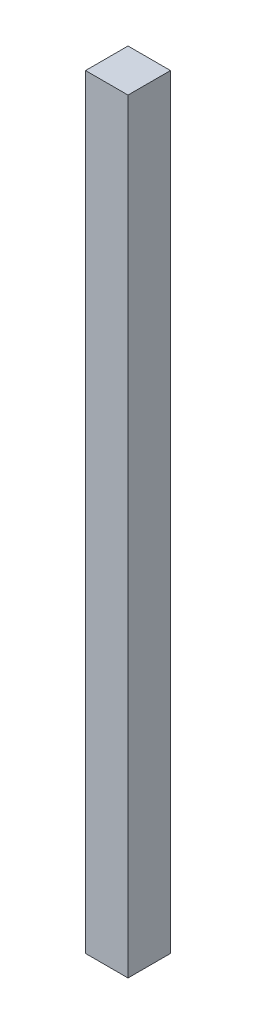
SolidWorks part; units mm, degrees
ref_plane "Front Plane" through (0, 0, 0) normal (0, 0, 1) x (1, 0, 0)
ref_plane "Top Plane" through (0, 0, 0) normal (0, 1, 0) x (1, 0, 0)
ref_plane "Right Plane" through (0, 0, 0) normal (1, 0, 0) x (0, 0, -1)
sketch "Sketch1" plane through (0, 0, 0) normal (0, 1, 0) x (1, 0, 0)
  line L1 (0, 0) -> (15, 0)
  line L2 (0, 0) -> (0, 15)
  line L3 (0, 15) -> (15, 15)
  line L4 (15, 0) -> (15, 15)
  dimension "D1" = 15
extrude "Boss-Extrude1" add sketch "Sketch1" along normal blind 270 contours L3 L4 L1 L2
